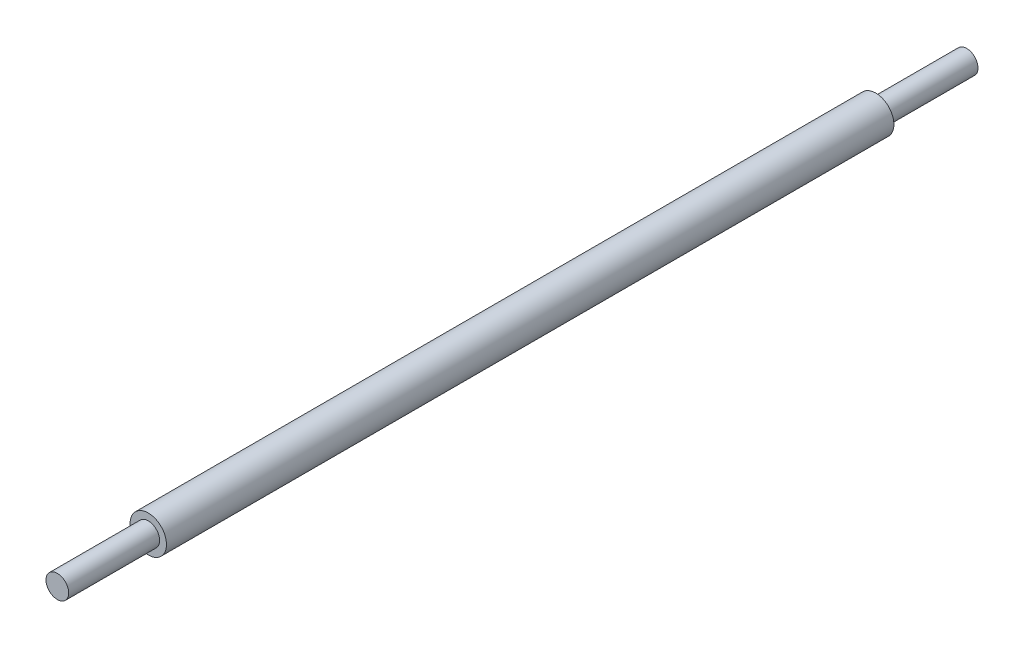
SolidWorks part; units mm, degrees
ref_plane "Front Plane" through (0, 0, 0) normal (0, 0, 1) x (1, 0, 0)
ref_plane "Top Plane" through (0, 0, 0) normal (0, 1, 0) x (1, 0, 0)
ref_plane "Right Plane" through (0, 0, 0) normal (1, 0, 0) x (0, 0, -1)
sketch "Sketch1" plane through (0, 0, 0) normal (0, 0, 1) x (1, 0, 0)
  circle A0 centre (0, 0) radius 5.08
  dimension "D1" = 10.16
extrude "Boss-Extrude1" add sketch "Sketch1" along normal mid plane 203.2
sketch "Sketch2" plane through (0, 0, 101.6) normal (0, 0, 1) x (1, 0, 0)
  circle A0 centre (0, 0) radius 3.175
  dimension "D1" = 6.35
extrude "Boss-Extrude2" add sketch "Sketch2" along normal blind 25.4
mirror "Mirror1" about plane through (0, 0, 0) normal (0, 0, 1) of "Boss-Extrude2"
scale "Scale1" scale about centroid uniform scaling yes scale factor 0.66
